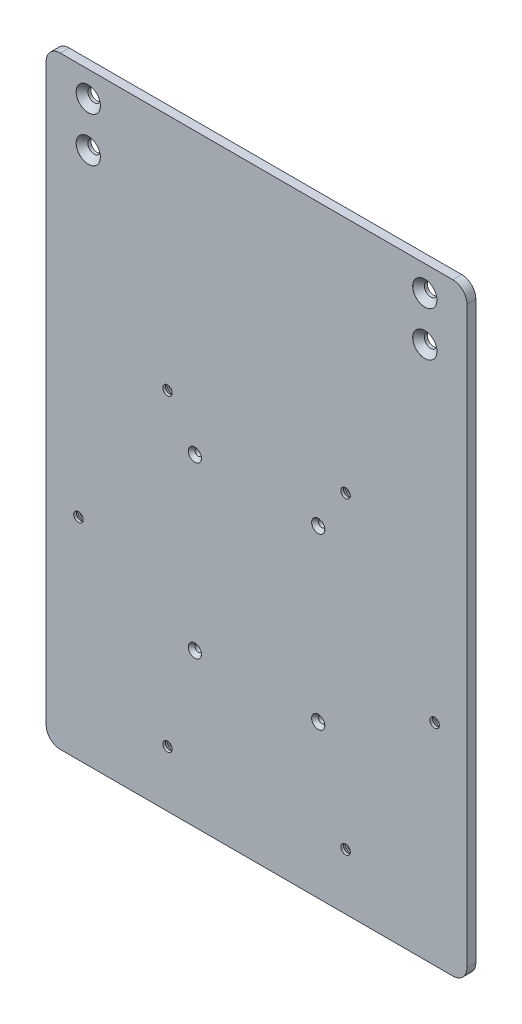
SolidWorks part; units mm, degrees
ref_plane "Front Plane" through (0, 0, 0) normal (0, 0, 1) x (1, 0, 0)
ref_plane "Top Plane" through (0, 0, 0) normal (0, 1, 0) x (1, 0, 0)
ref_plane "Right Plane" through (0, 0, 0) normal (1, 0, 0) x (0, 0, -1)
sketch "Sketch1" plane through (0, 0, 0) normal (0, 0, 1) x (1, 0, 0)
  line L0 (-51.4073, 374.7508) -> (-51.4073, 404.7508) construction
  line L2 (128.1124, 153.2208) -> (158.1124, 153.2208) construction
  line L4 (-51.4073, 404.7508) -> (158.1124, 404.7508)
  line L5 (-51.4073, 4.7508) -> (-51.4073, -25.2492) construction
  line L7 (158.1124, 404.7508) -> (158.1124, -25.2492)
  line L8 (-111.8876, 13.6408) -> (-141.8876, 13.6408) construction
  line L10 (158.1124, -25.2492) -> (-141.8876, -25.2492)
  line L11 (-141.8876, -25.2492) -> (-141.8876, 404.7508)
  line L12 (-141.8876, 404.7508) -> (-51.4073, 404.7508)
  dimension "D1" = 30
  dimension "D2" = 30
  dimension "D3" = 30
  dimension "D4" = 30
  dimension "D5" = 430
  dimension "D6" = 300
extrude "Boss-Extrude1" add sketch "Sketch1" along normal blind 6.35
fillet "Fillet1" radius 10 4 edges at (-141.8876, -25.2492, 3.175) (158.1124, -25.2492, 3.175) (158.1124, 404.7508, 3.175) (-141.8876, 404.7508, 3.175)
sketch "Sketch10" plane through (0, 0, 0) normal (0, 0, -1) x (-1, 0, 0)
  line L3 (-8.1124, 124.7508) -> (-71.6124, 234.736) construction
  line L6 (118.8876, 124.7508) -> (-135.1124, 124.7508) construction
  line L10 (-8.1124, 124.7508) -> (55.3876, 234.736) construction
  line L11 (-8.1124, 124.7508) -> (-71.6124, 14.7656) construction
  line L12 (-8.1124, 124.7508) -> (55.3876, 14.7656) construction
  circle A0 centre (-8.1124, 124.7508) radius 127
  dimension "D2" = 60
  dimension "D5" = 60
  dimension "D6" = 60
sketch "Sketch15" plane through (0, 0, 6.35) normal (0, 0, -1) x (-1, 0, 0)
  line L0 (-52.1124, 204.7508) -> (-52.1124, 83.7508) construction
  line L1 (-8.1124, 204.7508) -> (-8.1124, 404.7508) construction
  line L2 (-148.1124, 404.7508) -> (131.8876, 404.7508) construction
  line L6 (-52.1124, 204.7508) -> (35.8876, 204.7508) construction
  line L7 (35.8876, 204.7508) -> (35.8876, 83.7508) construction
  line L9 (-52.1124, 83.7508) -> (35.8876, 83.7508) construction
  dimension "D1" = 121
  dimension "D2" = 200
  dimension "D3" = 88
hole_wizard "CSK for 1/4 Flat Head Machine Screw2" positions "3DSketch6" profile "Sketch18" countersink size "1/4" standard "Ansi Inch" end condition through all
sketch3d "3DSketch6"
  point P0 (-55.3876, 234.736, 0)
  point P3 (71.6124, 234.736, 0)
  point P6 (135.1124, 124.7508, 0)
  point P9 (-118.8876, 124.7508, 0)
  point P12 (-55.3876, 14.7656, 0)
  point P15 (71.6124, 14.7656, 0)
sketch "Sketch18" plane through (-55.3876, 234.736, 0) normal (1, 0, 0) x (0, 1, 0)
  line L0 (0, 0) -> (0, 6.35)
  line L1 (0, 6.35) -> (3.3782, 6.35)
  line L2 (3.3782, 6.35) -> (3.3782, 4.5209)
  line L3 (3.3782, 4.5209) -> (6.4389, 1)
  line L4 (6.4389, 1) -> (6.4389, 0)
  line L6 (6.4389, 0) -> (0, 0)
  line L7 (-3.3782, 4.5209) -> (-6.4389, 1) construction
  line L11 (0, -6.35) -> (0, 107.95) construction
  dimension "Thru Hole Dia." = 6.7564
  dimension "Thru Hole Depth" = 6.35
  dimension "C'Sink Dia." = 12.8778
  dimension "C'Sink Angle" = 82
  dimension "Head Clearance" = 1
sketch "Sketch26" plane through (0, 0, 6.35) normal (0, 0, 1) x (1, 0, 0)
  line L0 (8.1124, 404.7508) -> (8.1124, 354.7508) construction
  line L1 (148.1124, 404.7508) -> (-131.8876, 404.7508) construction
  line L2 (-93.2372, 354.7508) -> (-93.2372, 386.5008) construction
  point P4 (128.1124, 306.5008)
  point P5 (128.1124, 274.7508)
  point P7 (-111.8876, 354.7508)
  point P11 (-111.8876, 386.5008)
  point P12 (128.1124, 386.5008)
  point P13 (128.1124, 354.7508)
  dimension "D1" = 50
  dimension "D2" = 31.75
hole_wizard "CSK for M8 Flat Head Machine Screw3" positions "3DSketch13" profile "Sketch28" countersink size "M8" standard "Ansi Metric" end condition through all
sketch3d "3DSketch13"
  point P0 (-111.8876, 386.5008, 6.35)
  point P3 (-111.8876, 354.7508, 6.35)
  point P6 (128.1124, 386.5008, 6.35)
  point P9 (128.1124, 354.7508, 6.35)
sketch "Sketch28" plane through (-111.8876, 386.5008, 6.35) normal (1, 0, 0) x (0, -1, 0)
  line L0 (0, 0) -> (0, 6.35)
  line L1 (0, 6.35) -> (4.5, 6.35)
  line L2 (4.5, 6.35) -> (4.5, 4.1894)
  line L3 (4.5, 4.1894) -> (8.65, 0.0394)
  line L4 (8.65, 0.0394) -> (8.65, 0)
  line L6 (8.65, 0) -> (0, 0)
  line L7 (-4.5, 4.1894) -> (-8.65, 0.0394) construction
  line L11 (0, -6.35) -> (0, 107.95) construction
  dimension "Thru Hole Dia." = 9
  dimension "Thru Hole Depth" = 6.35
  dimension "C'Sink Dia." = 17.3
  dimension "C'Sink Angle" = 90
  dimension "Head Clearance" = 0.0394
hole_wizard "CSK for M4 Flat Head Machine Screw1" positions "3DSketch15" profile "Sketch30" countersink size "M4" standard "Ansi Metric" end condition through all
sketch3d "3DSketch15"
  point P0 (-35.8876, 204.7508, 6.35)
  point P3 (52.1124, 204.7508, 6.35)
  point P6 (52.1124, 83.7508, 6.35)
  point P9 (-35.8876, 83.7508, 6.35)
sketch "Sketch30" plane through (-35.8876, 204.7508, 6.35) normal (1, 0, 0) x (0, -1, 0)
  line L0 (0, 0) -> (0, 6.35)
  line L1 (0, 6.35) -> (2.25, 6.35)
  line L2 (2.25, 6.35) -> (2.25, 2.45)
  line L3 (2.25, 2.45) -> (4.7, 0)
  line L5 (4.7, 0) -> (0, 0)
  line L6 (-2.25, 2.45) -> (-4.7, 0) construction
  line L11 (0, -6.35) -> (0, 107.95) construction
  dimension "Thru Hole Dia." = 4.5
  dimension "Thru Hole Depth" = 6.35
  dimension "Near C'Sink Dia." = 9.4
  dimension "Near C'Sink Angle" = 90
